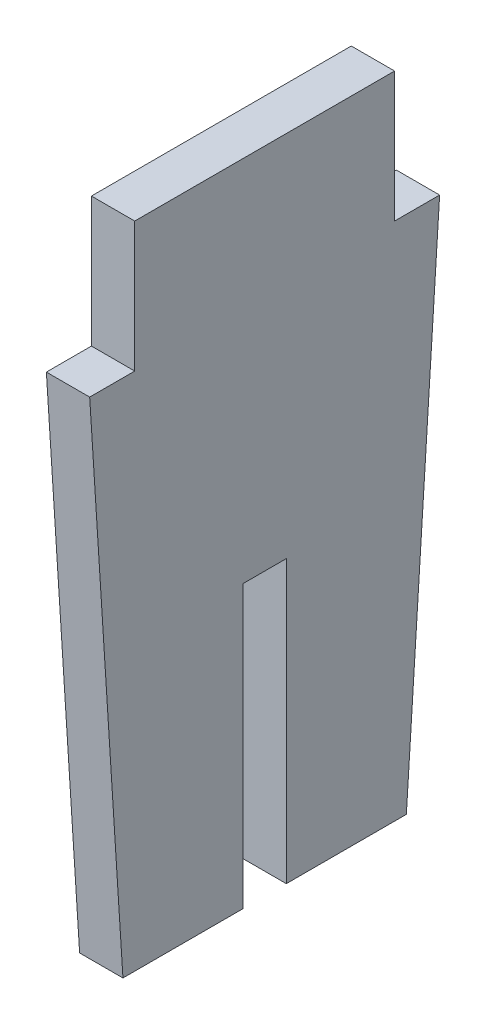
SolidWorks part; units mm, degrees
ref_plane "Front Plane" through (0, 0, 0) normal (0, 0, 1) x (1, 0, 0)
ref_plane "Top Plane" through (0, 0, 0) normal (0, 1, 0) x (1, 0, 0)
ref_plane "Right Plane" through (0, 0, 0) normal (1, 0, 0) x (0, 0, -1)
sketch "Sketch1" plane through (0, 0, 0) normal (1, 0, 0) x (0, 0, -1)
  line L0 (0, 55) -> (0, -55) construction
  line L1 (0, 47.625) -> (19.05, 47.625)
  line L2 (0, 47.625) -> (0, 38.1)
  line L3 (-3.302, 38.1) -> (22.352, 38.1) construction
  line L4 (19.05, 47.625) -> (19.05, 38.1)
  line L5 (0, 38.1) -> (-3.302, 38.1)
  line L6 (9.525, 38.1) -> (9.525, 6.35) construction
  line L7 (19.05, 38.1) -> (22.352, 38.1)
  line L8 (-1.27, 6.35) -> (20.32, 6.35) construction
  line L9 (-3.302, 38.1) -> (-1.27, 6.35)
  line L10 (22.352, 38.1) -> (20.32, 6.35)
  line L11 (20.32, 6.35) -> (19.9136, 0)
  line L12 (-1.27, 6.35) -> (-0.8636, 0)
  line L13 (-0.8636, 0) -> (7.9375, 0)
  line L14 (55, 0) -> (-55, 0) construction
  line L15 (11.1125, 0) -> (19.9136, 0)
  line L16 (11.1125, 20.6375) -> (7.9375, 20.6375)
  line L17 (11.1125, 20.6375) -> (11.1125, 0)
  line L19 (7.9375, 20.6375) -> (7.9375, 0)
  line L20 (11.1125, 20.6375) -> (7.9375, 0) construction
  line L21 (11.1125, 0) -> (7.9375, 20.6375) construction
  point P8 (9.525, 10.3187)
  dimension "D1" = 9.525
  dimension "D2" = 19.05
  dimension "D3" = 25.654
  dimension "D4" = 31.75
  dimension "D5" = 21.59
  dimension "D6" = 6.35
  dimension "D7" = 20.7772
  dimension "D8" = 20.7772
  dimension "D9" = 3.175
  dimension "D10" = 20.6375
  dimension "D11" = 47.625
extrude "Boss-Extrude1" add sketch "Sketch1" along normal blind 3.175
